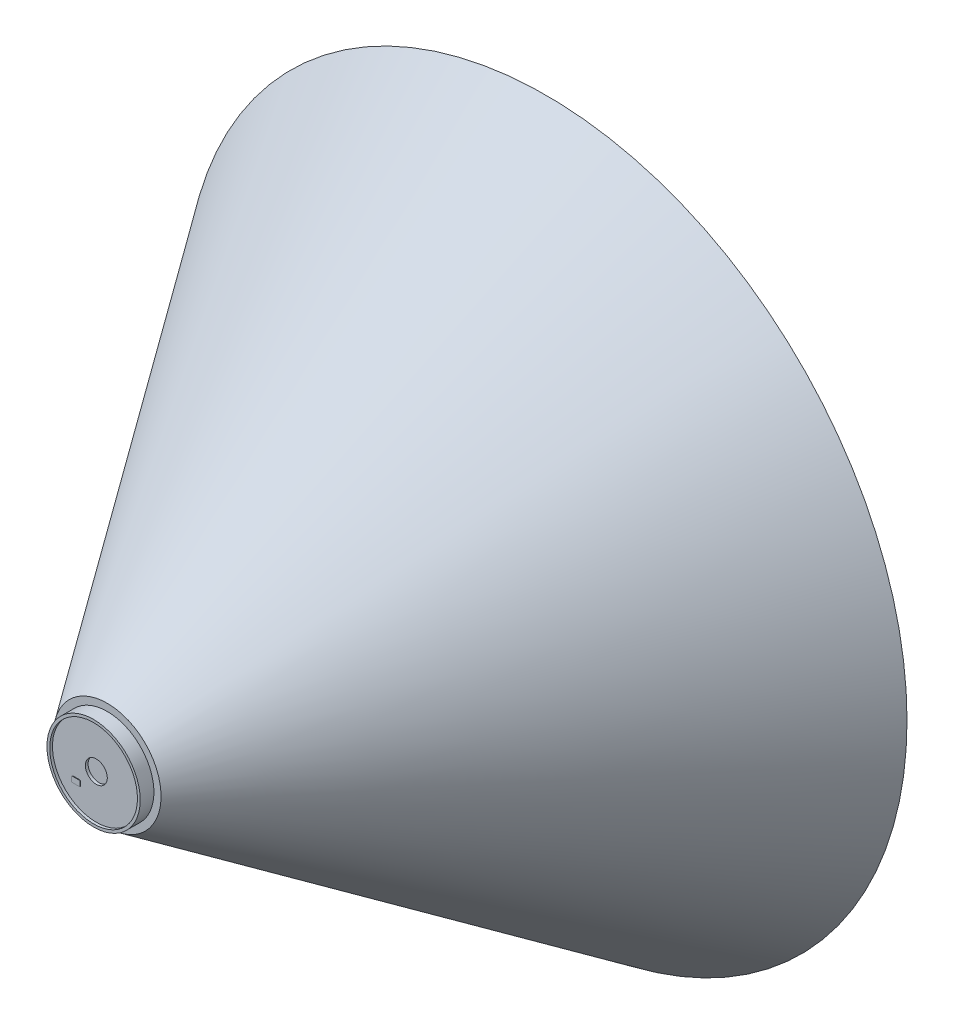
SolidWorks part; units mm, degrees
ref_plane "Alzado" through (0, 0, 0) normal (0, 0, 1) x (1, 0, 0)
ref_plane "Planta" through (0, 0, 0) normal (0, 1, 0) x (1, 0, 0)
ref_plane "Vista lateral" through (0, 0, 0) normal (1, 0, 0) x (0, 0, -1)
sketch "Croquis1" plane through (0, 0, 0) normal (0, 0, 1) x (1, 0, 0)
  circle A0 centre (0, 0) radius 400
  circle A1 centre (0, 0) radius 100
extrude "Saliente-Extruir1" add sketch "Croquis1" along normal blind 100
sketch "Croquis2" plane through (0, 0, 0) normal (0, 0, 1) x (1, 0, 0)
  circle A0 centre (0, 0) radius 425
  circle A1 centre (0, 0) radius 400
extrude "Saliente-Extruir2" add sketch "Croquis2" along normal blind 125 separate body
sketch "Croquis3" plane through (0, 0, 0) normal (0, 0, 1) x (1, 0, 0)
  circle A0 centre (0, 0) radius 100
extrude "Saliente-Extruir3" add sketch "Croquis3" along normal blind 75 separate body
sketch "Croquis5" plane through (0, 0, 100) normal (0, 0, 1) x (1, 0, 0)
  line L0 (0, 0) -> (-220, 0) construction
  line L1 (-220, 0) -> (-220, -140) construction
  line L3 (-220, -140) -> (-145, -140)
  line L4 (-220, -140) -> (-220, -190)
  line L5 (-220, -190) -> (-145, -190)
  line L6 (-145, -140) -> (-145, -190)
  dimension "D1" = 50
  dimension "D2" = 75
extrude "Saliente-Extruir4" add sketch "Croquis5" along normal blind 5
fillet "Redondeo1" radius 5 4 edges at (-220, -140, 102.5) (-145, -140, 102.5) (-145, -190, 102.5) (-220, -190, 102.5)
sketch "Croquis6" plane through (0, 0, 0) normal (0, 1, 0) x (1, 0, 0)
  line L0 (-490.1135, 0) -> (-3290.9436, 4000)
  line L1 (0, 0) -> (0, 4000) construction
  line L2 (0, 4000) -> (-3290.9436, 4000)
  line L3 (0, 0) -> (-490.1135, 0)
  line L4 (0, 0) -> (0, 4000)
revolve "Revolución2" add sketch "Croquis6" angle 360 about L4
